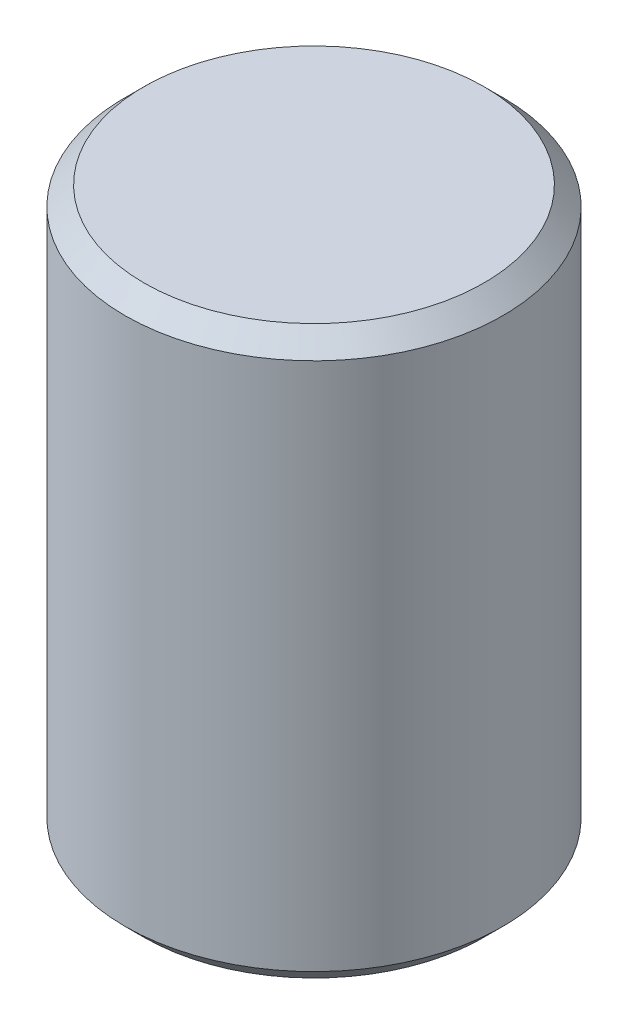
SolidWorks part; units mm, degrees
ref_plane "Front Plane" through (0, 0, 0) normal (0, 0, 1) x (1, 0, 0)
ref_plane "Top Plane" through (0, 0, 0) normal (0, 1, 0) x (1, 0, 0)
ref_plane "Right Plane" through (0, 0, 0) normal (1, 0, 0) x (0, 0, -1)
sketch "Sketch1" plane through (0, 0, 0) normal (0, 1, 0) x (1, 0, 0)
  circle A0 centre (-14.0149, 2.4643) radius 5
  dimension "D1" = 10
extrude "Peg" add sketch "Sketch1" along normal blind 15
chamfer "Peg Chamfer" distance 0.5 angle 45 2 edges at (-14.0149, 0, 2.5357) (-14.0149, 15, 2.5357)
